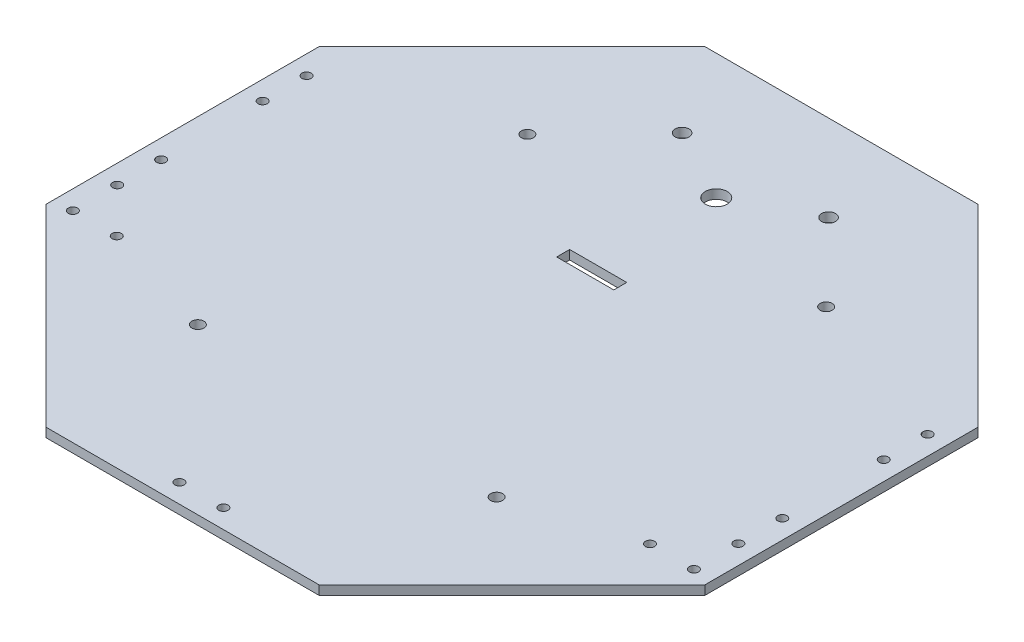
SolidWorks part; units mm, degrees
ref_plane "Front Plane" through (0, 0, 0) normal (0, 0, 1) x (1, 0, 0)
ref_plane "Top Plane" through (0, 0, 0) normal (0, 1, 0) x (1, 0, 0)
ref_plane "Right Plane" through (0, 0, 0) normal (1, 0, 0) x (0, 0, -1)
sketch "Sketch1" plane through (0, 0, 0) normal (0, 1, 0) x (1, 0, 0)
  line L1 (0, 139.7) -> (152.4, 139.7) construction
  line L2 (152.4, 139.7) -> (152.4, 0) construction
  line L4 (76.2, 139.7) -> (76.2, 0) construction
  line L8 (24.384, 0) -> (24.384, 12.7) construction
  line L9 (1.3179, 69.85) -> (152.4, 69.85) construction
  line L10 (0, 139.7) -> (0, 0) construction
  line L11 (0, 0) -> (152.4, 0) construction
  line L12 (24.384, 12.7) -> (0, 12.7) construction
  line L13 (128.016, 0) -> (128.016, 12.7) construction
  line L14 (128.016, 12.7) -> (152.4, 12.7) construction
  line L15 (128.016, 127) -> (152.4, 127) construction
  line L16 (128.016, 139.7) -> (128.016, 127) construction
  line L17 (24.384, 139.7) -> (24.384, 127) construction
  line L18 (24.384, 127) -> (0, 127) construction
  line L19 (76.2, -44.45) -> (76.2, -30.45) construction
  line L20 (-38.1, 69.85) -> (190.5, 69.85) construction
  line L21 (28.8554, 184.15) -> (123.5446, 184.15)
  line L22 (190.5, 22.5054) -> (190.5, 117.1946)
  line L23 (28.8554, -44.45) -> (123.5446, -44.45)
  line L24 (-38.1, 22.5054) -> (-38.1, 117.1946)
  line L29 (28.8554, 184.15) -> (-24.1, 131.1946)
  line L30 (123.5446, 184.15) -> (176.5, 131.1946)
  line L31 (-38.1, 22.5054) -> (-30.1, 14.5054)
  line L32 (190.5, 22.5054) -> (182.5, 14.5054)
  line L33 (-38.1, 69.85) -> (-24.1, 69.85) construction
  line L34 (-24.1, 27.94) -> (-24.1, 111.76) construction
  line L35 (-30.1, 125.1946) -> (-38.1, 117.1946)
  line L40 (-24.1, 8.5054) -> (14.8554, -30.45)
  line L45 (-4.6223, -10.9723) -> (157.0223, 150.6723) construction
  line L46 (137.5446, -30.45) -> (131.5446, -36.45)
  line L47 (76.2, -44.45) -> (76.2, -30.45) construction
  line L55 (190.5, 69.85) -> (176.5, 69.85) construction
  line L62 (20.8554, -36.45) -> (28.8554, -44.45)
  line L63 (131.5446, -36.45) -> (123.5446, -44.45)
  line L64 (176.5, 8.5054) -> (137.5446, -30.45)
  line L65 (182.5, 125.1946) -> (190.5, 117.1946)
  line L66 (14.8554, -30.45) -> (20.8554, -36.45)
  line L67 (76.2, 0) -> (76.2, 184.15) construction
  line L68 (182.5, 125.1946) -> (176.5, 131.1946)
  line L69 (182.5, 14.5054) -> (176.5, 8.5054)
  line L70 (-24.1, 131.1946) -> (-30.1, 125.1946)
  line L71 (-30.1, 14.5054) -> (-24.1, 8.5054)
  circle A0 centre (24.384, 12.7) radius 2.0828
  circle A1 centre (128.016, 12.7) radius 2.0828
  circle A2 centre (128.016, 127) radius 2.0828
  circle A3 centre (24.384, 127) radius 2.0828
  point P28 (76.2, 69.85)
  point P31 (76.2, 69.85)
  point P34 (76.2, 184.15)
  point P37 (190.5, 69.85)
  point P40 (76.2, -44.45)
  point P46 (-24.1, 69.85)
  point P55 (76.2, 69.85)
  dimension "D3" = 24.384
  dimension "D1" = 139.7
  dimension "D2" = 152.4
  dimension "D4" = 12.7
  dimension "D5" = 94.6892
  dimension "D6" = 228.6
extrude "Boss-Extrude1" add sketch "Sketch1" along normal blind 3.175
sketch "Sketch2" plane through (0, 3.175, 0) normal (0, 1, 0) x (1, 0, 0)
  line L21 (-31.5214, 106.3131) -> (-31.5214, 91.0731) construction
  line L22 (-31.5214, 40.6396) -> (-31.5214, 55.8796) construction
  line L23 (-31.5214, 25.2303) -> (-16.2814, 25.2303) construction
  line L24 (83.82, -37.8714) -> (68.58, -37.8714) construction
  line L25 (76.2, -44.45) -> (76.2, 179.1379) construction
  line L26 (28.8554, -44.45) -> (123.5446, -44.45) construction
  line L35 (183.9214, 25.2303) -> (168.6814, 25.2303) construction
  line L36 (183.9214, 40.6396) -> (183.9214, 55.8796) construction
  line L37 (183.9214, 106.3131) -> (183.9214, 91.0731) construction
  point P19 (76.2, -37.8714)
hole_wizard "M3 Clearance Hole1" positions "Sketch3" profile "Sketch4" hole size "M3" standard "ANSI Metric" end condition through all
sketch "Sketch3" plane through (0, 3.175, 0) normal (0, 1, 0) x (1, 0, 0)
  point P0 (-31.5214, 106.3131)
  point P3 (-31.5214, 91.0731)
  point P6 (-31.5214, 55.8796)
  point P9 (-31.5214, 40.6396)
  point P12 (-31.5214, 25.2303)
  point P15 (-16.2814, 25.2303)
  point P18 (68.58, -37.8714)
  point P21 (83.82, -37.8714)
  point P24 (183.9214, 25.2303)
  point P27 (168.6814, 25.2303)
  point P30 (183.9214, 40.6396)
  point P33 (183.9214, 55.8796)
  point P36 (183.9214, 91.0731)
  point P39 (183.9214, 106.3131)
sketch "Sketch4" plane through (-31.5214, 3.175, -106.3131) normal (1, 0, 0) x (0, 0, 1)
  line L0 (0, 0) -> (0, 3.175)
  line L1 (0, 3.175) -> (1.6, 3.175)
  line L2 (1.6, 3.175) -> (1.6, 0)
  line L5 (1.6, 0) -> (0, 0)
  line L11 (0, -6.35) -> (0, 107.95) construction
  dimension "Thru Hole Dia." = 3.2
  dimension "Thru Hole Depth" = 3.175
sketch "Sketch5" plane through (0, 3.175, 0) normal (0, 1, 0) x (1, 0, 0)
  line L0 (-38.1, 69.85) -> (190.5, 69.85) construction
  line L3 (86.1, 99.75) -> (66.3, 99.75)
  line L4 (86.1, 99.75) -> (86.1, 95.25)
  line L5 (86.1, 95.25) -> (66.3, 95.25)
  line L6 (66.3, 99.75) -> (66.3, 95.25)
  line L7 (86.1, 105.2961) -> (66.3, 100.7961) construction
  line L8 (86.1, 100.7961) -> (66.3, 105.2961) construction
  line L9 (-38.1, 117.1946) -> (-38.1, 22.5054) construction
  line L10 (190.5, 22.5054) -> (190.5, 117.1946) construction
  dimension "D1" = 19.8
  dimension "D2" = 4.5
  dimension "D3" = 25.4
extrude "Cut-Extrude1" cut sketch "Sketch5" against normal through all
sketch "Sketch6" plane through (0, 3.175, 0) normal (0, 1, 0) x (1, 0, 0)
  line L0 (190.5, 69.85) -> (-38.1, 69.85) construction
  line L1 (190.5, 22.5054) -> (190.5, 117.1946) construction
  line L2 (-38.1, 117.1946) -> (-38.1, 22.5054) construction
sketch "Sketch7" plane through (0, 3.175, 0) normal (0, 1, 0) x (1, 0, 0)
  line L0 (76.2, 154.2636) -> (50.8, 154.2636) construction
  line L1 (76.2, -44.45) -> (76.2, 179.1379) construction
  line L2 (76.2, 179.1379) -> (76.2, 133.7812) construction
  circle A0 centre (50.8, 154.2636) radius 2.413
  circle A1 centre (101.6, 154.2636) radius 2.413
extrude "Cut-Extrude2" cut sketch "Sketch7" against normal through all
sketch "Sketch8" plane through (0, 3.175, 0) normal (0, 1, 0) x (1, 0, 0)
  line L0 (76.2, -44.45) -> (76.2, 179.1379) construction
  circle A0 centre (76.2, 140.698) radius 3.81
extrude "Cut-Extrude3" cut sketch "Sketch8" against normal through all
